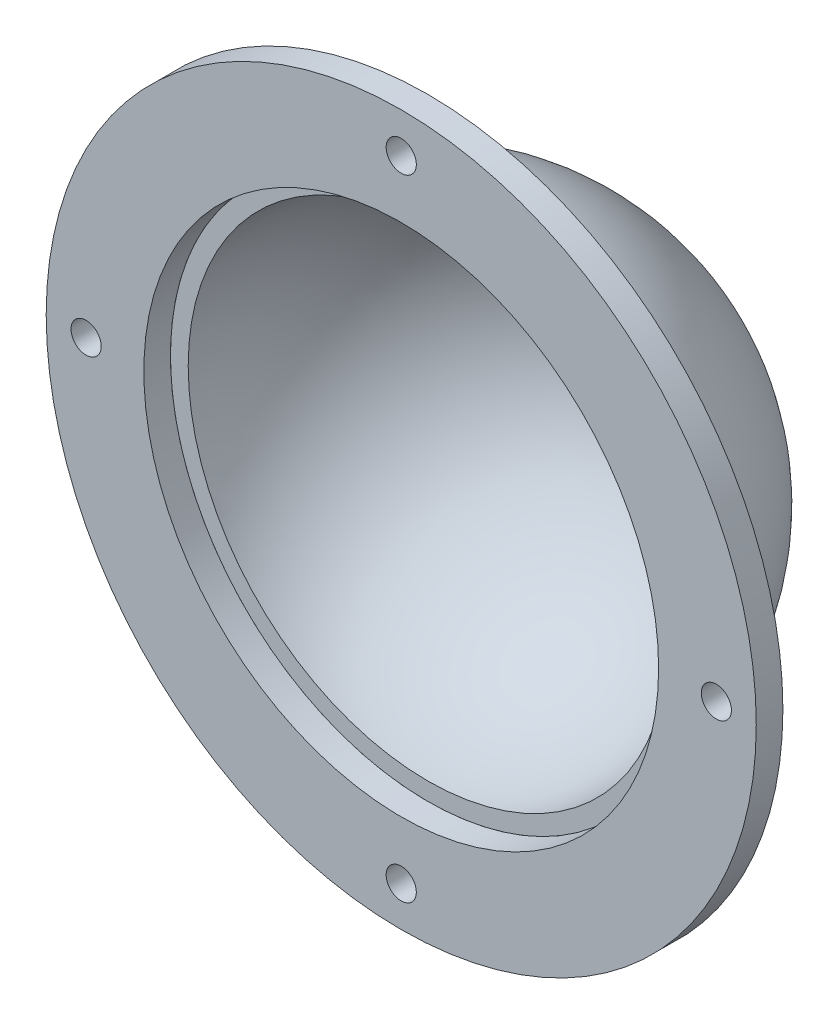
SolidWorks part; units mm, degrees
material "ABS"
ref_plane "前视基准面" through (0, 0, 0) normal (0, 0, 1) x (1, 0, 0)
ref_plane "上视基准面" through (0, 0, 0) normal (0, 1, 0) x (1, 0, 0)
ref_plane "右视基准面" through (0, 0, 0) normal (1, 0, 0) x (0, 0, -1)
sketch "草图1" plane through (0, 0, 0) normal (0, 0, 1) x (1, 0, 0)
  line L0 (0, 35.5) -> (0, 0) construction
  line L1 (0, 0) -> (35.5, 0) construction
  circle A0 centre (0, 0) radius 40
  circle A1 centre (0, 0) radius 35.5 construction
  circle A2 centre (0, 35.5) radius 1.7
  circle A3 centre (35.5, 0) radius 1.7
  circle A4 centre (0, -35.5) radius 1.7
  circle A5 centre (-35.5, 0) radius 1.7
  circle A6 centre (0, 0) radius 29
  point P16 (0, 0)
  dimension "D1" = 80
  dimension "D3" = 3.4
  dimension "D5" = 90
  dimension "D2" = 4.5
  dimension "D6" = 6.5
  dimension "D4" = 4
extrude "凸台-拉伸1" add sketch "草图1" along normal blind 3
sketch "草图2" plane through (0, 0, 0) normal (0, 1, 0) x (1, 0, 0)
  line L1 (29, 0) -> (-29, 0) construction
  line L2 (29, 0) -> (-29, 0)
  line L3 (0, 29) -> (0, 0.504)
  arc A0 (0, 29) -> (29, 0) centre (0, 0) cw
  arc A1 (0, 27) -> (27, 0) centre (0, 0) cw
  dimension "D1" = 2
revolve "旋转1" add sketch "草图2" angle 360 about L3
